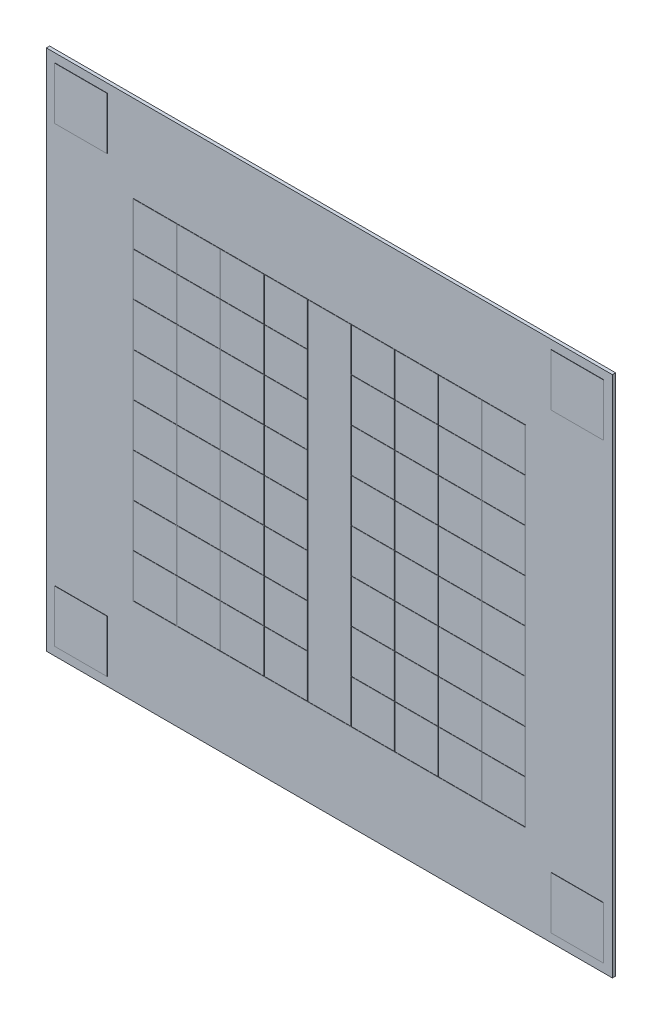
SolidWorks part; units mm, degrees
ref_plane "前视基准面" through (0, 0, 0) normal (0, 0, 1) x (1, 0, 0)
ref_plane "上视基准面" through (0, 0, 0) normal (0, 1, 0) x (1, 0, 0)
ref_plane "右视基准面" through (0, 0, 0) normal (1, 0, 0) x (0, 0, -1)
other "Configuration Table"
sketch "草图1" plane through (0, 0, 0) normal (0, 0, 1) x (1, 0, 0)
  line L1 (-260, -240) -> (260, -240)
  line L2 (-260, -240) -> (-260, 240)
  line L3 (-260, 240) -> (260, 240)
  line L4 (260, -240) -> (260, 240)
extrude "520x480棋盘与码区域" add sketch "草图1" along normal blind 3 from offset 3
sketch "草图2" plane through (0, 0, 0) normal (0, 0, 1) x (1, 0, 0)
  line L1 (-180.2, -160) -> (-179.8, -160)
  line L2 (-180.2, -160) -> (-180.2, 160)
  line L3 (-180.2, 160) -> (-179.8, 160)
  line L4 (-179.8, -160) -> (-179.8, 160)
  line L6 (-140.2, -160) -> (-139.8, -160)
  line L7 (-140.2, -160) -> (-140.2, 160)
  line L8 (-140.2, 160) -> (-139.8, 160)
  line L9 (-139.8, -160) -> (-139.8, 160)
  line L11 (-100.2, -160) -> (-99.8, -160)
  line L12 (-100.2, -160) -> (-100.2, 160)
  line L13 (-100.2, 160) -> (-99.8, 160)
  line L14 (-99.8, -160) -> (-99.8, 160)
  line L16 (-60.2, -160) -> (-59.8, -160)
  line L17 (-60.2, -160) -> (-60.2, 160)
  line L18 (-60.2, 160) -> (-59.8, 160)
  line L19 (-59.8, -160) -> (-59.8, 160)
  line L21 (-20.2, -160) -> (-19.8, -160)
  line L22 (-20.2, -160) -> (-20.2, 160)
  line L23 (-20.2, 160) -> (-19.8, 160)
  line L24 (-19.8, -160) -> (-19.8, 160)
  line L26 (19.8, -160) -> (20.2, -160)
  line L27 (19.8, -160) -> (19.8, 160)
  line L28 (19.8, 160) -> (20.2, 160)
  line L29 (20.2, -160) -> (20.2, 160)
  line L31 (59.8, -160) -> (60.2, -160)
  line L32 (59.8, -160) -> (59.8, 160)
  line L33 (59.8, 160) -> (60.2, 160)
  line L34 (60.2, -160) -> (60.2, 160)
  line L36 (99.8, -160) -> (100.2, -160)
  line L37 (99.8, -160) -> (99.8, 160)
  line L38 (99.8, 160) -> (100.2, 160)
  line L39 (100.2, -160) -> (100.2, 160)
  line L41 (139.8, -160) -> (140.2, -160)
  line L42 (139.8, -160) -> (139.8, 160)
  line L43 (139.8, 160) -> (140.2, 160)
  line L44 (140.2, -160) -> (140.2, 160)
  line L46 (179.8, -160) -> (180.2, -160)
  line L47 (179.8, -160) -> (179.8, 160)
  line L48 (179.8, 160) -> (180.2, 160)
  line L49 (180.2, -160) -> (180.2, 160)
extrude "十条横线" add sketch "草图2" along normal blind 0.2
sketch "草图3" plane through (0, 0, 0) normal (0, 0, 1) x (1, 0, 0)
  line L1 (-180, -160.2) -> (180, -160.2)
  line L2 (-180, -160.2) -> (-180, -159.8)
  line L3 (-180, -159.8) -> (180, -159.8)
  line L4 (180, -160.2) -> (180, -159.8)
  line L6 (-180, -120.2) -> (-20, -120.2)
  line L7 (-180, -120.2) -> (-180, -119.8)
  line L8 (-180, -119.8) -> (-20, -119.8)
  line L9 (-20, -120.2) -> (-20, -119.8)
  line L11 (20, -120.2) -> (180, -120.2)
  line L12 (20, -120.2) -> (20, -119.8)
  line L13 (20, -119.8) -> (180, -119.8)
  line L14 (180, -120.2) -> (180, -119.8)
  line L16 (-180, -80.2) -> (-20, -80.2)
  line L17 (-180, -80.2) -> (-180, -79.8)
  line L18 (-180, -79.8) -> (-20, -79.8)
  line L19 (-20, -80.2) -> (-20, -79.8)
  line L21 (20, -80.2) -> (180, -80.2)
  line L22 (20, -80.2) -> (20, -79.8)
  line L23 (20, -79.8) -> (180, -79.8)
  line L24 (180, -80.2) -> (180, -79.8)
  line L26 (-180, -40.2) -> (-20, -40.2)
  line L27 (-180, -40.2) -> (-180, -39.8)
  line L28 (-180, -39.8) -> (-20, -39.8)
  line L29 (-20, -40.2) -> (-20, -39.8)
  line L31 (20, -40.2) -> (180, -40.2)
  line L32 (20, -40.2) -> (20, -39.8)
  line L33 (20, -39.8) -> (180, -39.8)
  line L34 (180, -40.2) -> (180, -39.8)
  line L36 (-180, -0.2) -> (-20, -0.2)
  line L37 (-180, -0.2) -> (-180, 0.2)
  line L38 (-180, 0.2) -> (-20, 0.2)
  line L39 (-20, -0.2) -> (-20, 0.2)
  line L41 (20, -0.2) -> (180, -0.2)
  line L42 (20, -0.2) -> (20, 0.2)
  line L43 (20, 0.2) -> (180, 0.2)
  line L44 (180, -0.2) -> (180, 0.2)
  line L46 (-180, 39.8) -> (-20, 39.8)
  line L47 (-180, 39.8) -> (-180, 40.2)
  line L48 (-180, 40.2) -> (-20, 40.2)
  line L49 (-20, 39.8) -> (-20, 40.2)
  line L51 (20, 39.8) -> (180, 39.8)
  line L52 (20, 39.8) -> (20, 40.2)
  line L53 (20, 40.2) -> (180, 40.2)
  line L54 (180, 39.8) -> (180, 40.2)
  line L56 (-180, 79.8) -> (-20, 79.8)
  line L57 (-180, 79.8) -> (-180, 80.2)
  line L58 (-180, 80.2) -> (-20, 80.2)
  line L59 (-20, 79.8) -> (-20, 80.2)
  line L61 (20, 79.8) -> (180, 79.8)
  line L62 (20, 79.8) -> (20, 80.2)
  line L63 (20, 80.2) -> (180, 80.2)
  line L64 (180, 79.8) -> (180, 80.2)
  line L66 (-180, 119.8) -> (-20, 119.8)
  line L67 (-180, 119.8) -> (-180, 120.2)
  line L68 (-180, 120.2) -> (-20, 120.2)
  line L69 (-20, 119.8) -> (-20, 120.2)
  line L71 (20, 119.8) -> (180, 119.8)
  line L72 (20, 119.8) -> (20, 120.2)
  line L73 (20, 120.2) -> (180, 120.2)
  line L74 (180, 119.8) -> (180, 120.2)
  line L76 (-180, 159.8) -> (180, 159.8)
  line L77 (-180, 159.8) -> (-180, 160.2)
  line L78 (-180, 160.2) -> (180, 160.2)
  line L79 (180, 159.8) -> (180, 160.2)
extrude "九列和河界" add sketch "草图3" along normal blind 0.2
sketch "草图4" plane through (0, 0, 0) normal (0, 0, 1) x (1, 0, 0)
  line L1 (-252, -232) -> (-204, -232)
  line L2 (-252, -232) -> (-252, -184)
  line L3 (-252, -184) -> (-204, -184)
  line L4 (-204, -232) -> (-204, -184)
  line L6 (-252, 184) -> (-204, 184)
  line L7 (-252, 184) -> (-252, 232)
  line L8 (-252, 232) -> (-204, 232)
  line L9 (-204, 184) -> (-204, 232)
  line L11 (204, -232) -> (252, -232)
  line L12 (204, -232) -> (204, -184)
  line L13 (204, -184) -> (252, -184)
  line L14 (252, -232) -> (252, -184)
  line L16 (204, 184) -> (252, 184)
  line L17 (204, 184) -> (204, 232)
  line L18 (204, 232) -> (252, 232)
  line L19 (252, 184) -> (252, 232)
extrude "四块48mm角标位置" add sketch "草图4" along normal blind 0.3
